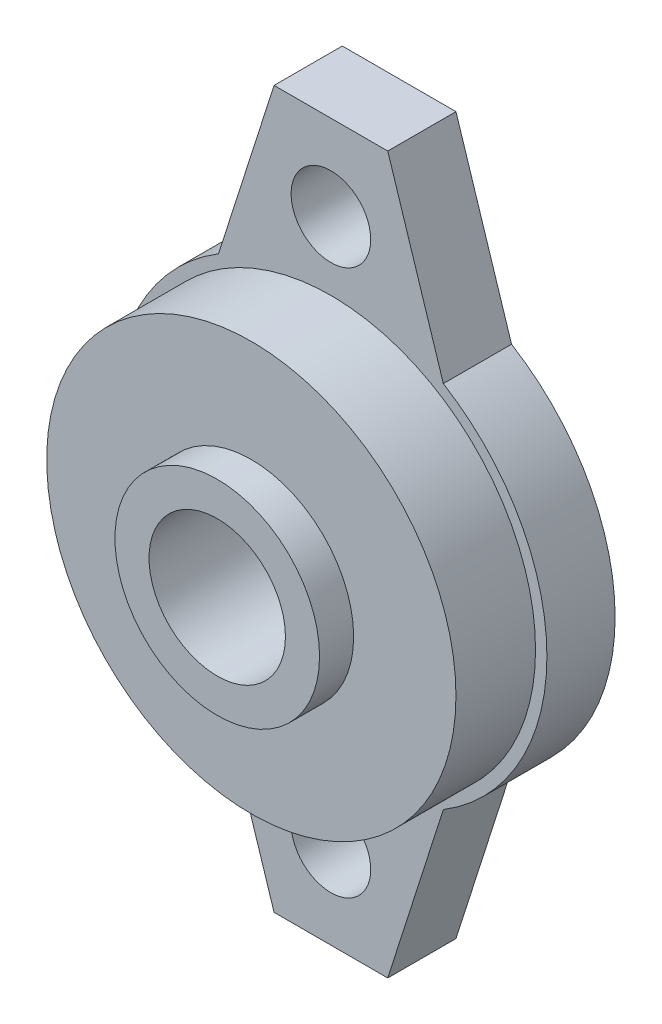
SolidWorks part; units mm, degrees
ref_plane "前基準面" through (0, 0, 0) normal (0, 0, 1) x (1, 0, 0)
ref_plane "上基準面" through (0, 0, 0) normal (0, 1, 0) x (1, 0, 0)
ref_plane "右基準面" through (0, 0, 0) normal (1, 0, 0) x (0, 0, -1)
sketch "草圖1" plane through (0, 0, 0) normal (0, 0, 1) x (1, 0, 0)
  line L0 (0, 0) -> (0, 24) construction
  line L1 (0, 24) -> (0, 31.5) construction
  line L2 (0, 0) -> (0, -24) construction
  line L3 (0, -24) -> (0, -31.5) construction
  line L4 (-5, 31.5) -> (5, 31.5)
  line L5 (-5, -31.5) -> (5, -31.5)
  line L6 (0, 19) -> (-9, 19) construction
  line L7 (0, 19) -> (9, 19) construction
  line L10 (-5, 31.5) -> (-9.8883, 16.2241)
  line L12 (5, 31.5) -> (9.8883, 16.2241)
  line L13 (-5, -31.5) -> (-9.8883, -16.2241)
  line L14 (5, -31.5) -> (9.8883, -16.2241)
  line L15 (0, -19) -> (-9, -19) construction
  line L16 (0, -19) -> (9, -19) construction
  circle A0 centre (0, 24) radius 3.5
  circle A1 centre (0, -24) radius 3.5
  circle A2 centre (0, 0) radius 6
  arc A5 (9.8883, -16.2241) -> (9.8883, 16.2241) centre (0, 0) ccw
  arc A6 (-9.8883, 16.2241) -> (-9.8883, -16.2241) centre (0, 0) ccw
  point P14 (0, 31.5)
  dimension "D3" = 7
  dimension "D4" = 12
  dimension "D5" = 38
  dimension "D6" = 9
  dimension "D1" = 48
  dimension "D2" = 63
  dimension "D7" = 10
extrude "填料-伸長1" add sketch "草圖1" along normal blind 6
ref_plane "平面1" through (0, 0, 6) normal (0, 0, 1) x (1, 0, 0)
sketch "草圖2" plane through (0, 0, 6) normal (0, 0, 1) x (1, 0, 0)
  circle A0 centre (0, 0) radius 18
  dimension "D1" = 36
extrude "填料-伸長2" add sketch "草圖2" along normal blind 7
ref_plane "平面2" through (0, 0, 13) normal (0, 0, 1) x (1, 0, 0)
sketch "草圖3" plane through (0, 0, 13) normal (0, 0, 1) x (1, 0, 0)
  circle A0 centre (0, 0) radius 9
  dimension "D1" = 18
extrude "填料-伸長3" add sketch "草圖3" along normal blind 3 contours A0
ref_plane "平面3" through (0, 0, 16) normal (0, 0, 1) x (1, 0, 0)
sketch "草圖4" plane through (0, 0, 16) normal (0, 0, 1) x (1, 0, 0)
  circle A0 centre (0, 0) radius 6
  dimension "D1" = 12
extrude "除料-伸長1" cut sketch "草圖4" against normal through all
